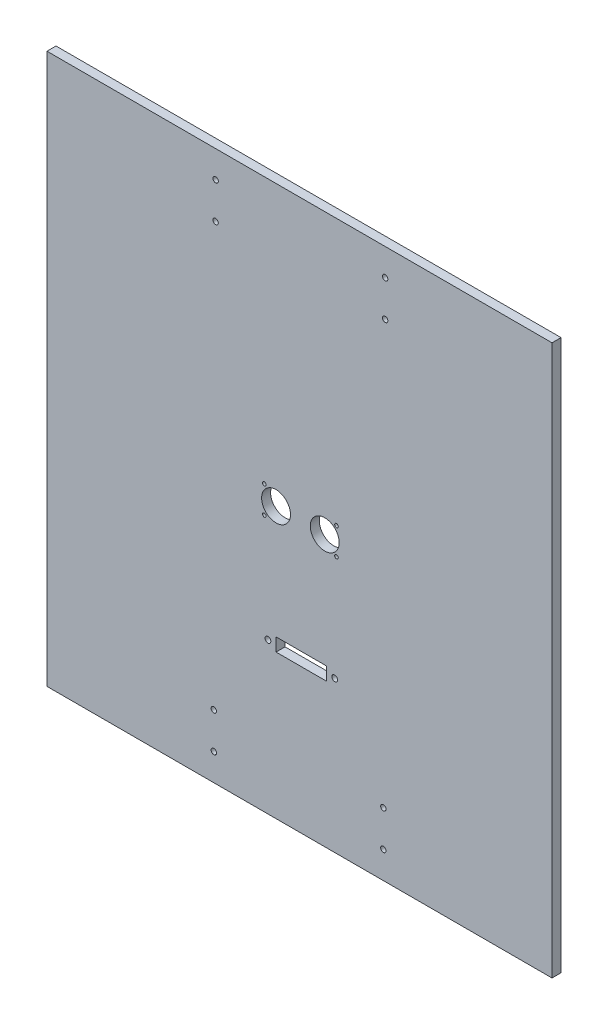
SolidWorks part; units mm, degrees
ref_plane "Plan de face" through (0, 0, 0) normal (0, 0, 1) x (1, 0, 0)
ref_plane "Plan de dessus" through (0, 0, 0) normal (0, 1, 0) x (1, 0, 0)
ref_plane "Plan de droite" through (0, 0, 0) normal (1, 0, 0) x (0, 0, -1)
sketch "Esquisse1" plane through (0, 0, 0) normal (0, 0, 1) x (1, 0, 0)
  line L1 (0, 0) -> (280, 0)
  line L2 (0, 0) -> (0, 305)
  line L3 (0, 305) -> (280, 305)
  line L4 (280, 0) -> (280, 305)
  dimension "D1" = 305
  dimension "D2" = 280
extrude "Boss.-Extru.1" add sketch "Esquisse1" along normal blind 5
sketch "Esquisse2" plane through (0, 0, 5) normal (0, 0, 1) x (1, 0, 0)
  circle A0 centre (92.5, 35) radius 1.5
  circle A1 centre (92.5, 15) radius 1.5
  circle A2 centre (186.5, 35) radius 1.5
  circle A3 centre (186.5, 15) radius 1.5
  dimension "D1" = 3
  dimension "D2" = 3
  dimension "D3" = 3
  dimension "D4" = 3
extrude "Enlèv. mat.-Extru.1" cut sketch "Esquisse2" against normal through all
sketch "Esquisse3" plane through (0, 0, 5) normal (0, 0, 1) x (1, 0, 0)
  circle A0 centre (187.5, 270) radius 1.5
  circle A1 centre (187.5, 290) radius 1.5
  circle A2 centre (93.5, 270) radius 1.5
  circle A3 centre (93.5, 290) radius 1.5
  circle A4 centre (187.5, 290) radius 1.5 construction
  dimension "D1" = 3
  dimension "D2" = 3
  dimension "D3" = 3
  dimension "D4" = 3
  dimension "D5" = 0
extrude "Enlèv. mat.-Extru.2" cut sketch "Esquisse3" against normal through all
sketch "Esquisse4" plane through (0, 0, 0) normal (0, 0, -1) x (-1, 0, 0)
  line L0 (0, 0) -> (-280, 0) construction
  line L1 (-155, 87.3) -> (-127, 87.3)
  line L2 (-155, 87.3) -> (-155, 80)
  line L3 (-155, 80) -> (-127, 80)
  line L4 (-127, 87.3) -> (-127, 80)
  line L5 (-280, 0) -> (-280, 305) construction
  line L6 (-180.5491, 83.65) -> (-87.7218, 83.65) construction
  circle A0 centre (-159.5, 83.65) radius 1.6
  circle A1 centre (-122.5, 83.65) radius 1.6
  point P4 (-141, 80)
  point P9 (-155, 83.65)
  dimension "D6" = 3.2
  dimension "D7" = 3.2
  dimension "D8" = 4.5
  dimension "D1" = 7.3
  dimension "D2" = 28
  dimension "D3" = 80
  dimension "D4" = 125
  dimension "D5" = 3.65
  dimension "D9" = 4.5
extrude "Enlèv. mat.-Extru.3" cut sketch "Esquisse4" against normal through all
sketch "Esquisse5" plane through (0, 0, 0) normal (0, 0, -1) x (-1, 0, 0)
  line L0 (0, 305) -> (0, 0) construction
  line L2 (0, 0) -> (-280, 0) construction
  circle A0 centre (-154, 150) radius 8
  circle A1 centre (-127, 150) radius 8
  circle A2 centre (-160.5026, 157.4915) radius 1
  circle A3 centre (-120.5026, 157.5151) radius 1
  circle A4 centre (-120.4988, 142.502) radius 1
  circle A5 centre (-160.4988, 142.4915) radius 1
  dimension "D1" = 16
  dimension "D2" = 16
  dimension "D3" = 27
  dimension "D4" = 127
  dimension "D5" = 150
  dimension "D6" = 150
  dimension "D7" = 2
  dimension "D8" = 2
  dimension "D9" = 2
  dimension "D10" = 2
  dimension "D11" = 40
  dimension "D12" = 15
  dimension "D13" = 34.33
  dimension "D14" = 34.33
  dimension "D15" = 34.33
  dimension "D16" = 34.33
  dimension "D17" = 40
  dimension "D18" = 9.92
extrude "Enlèv. mat.-Extru.4" cut sketch "Esquisse5" against normal through all
